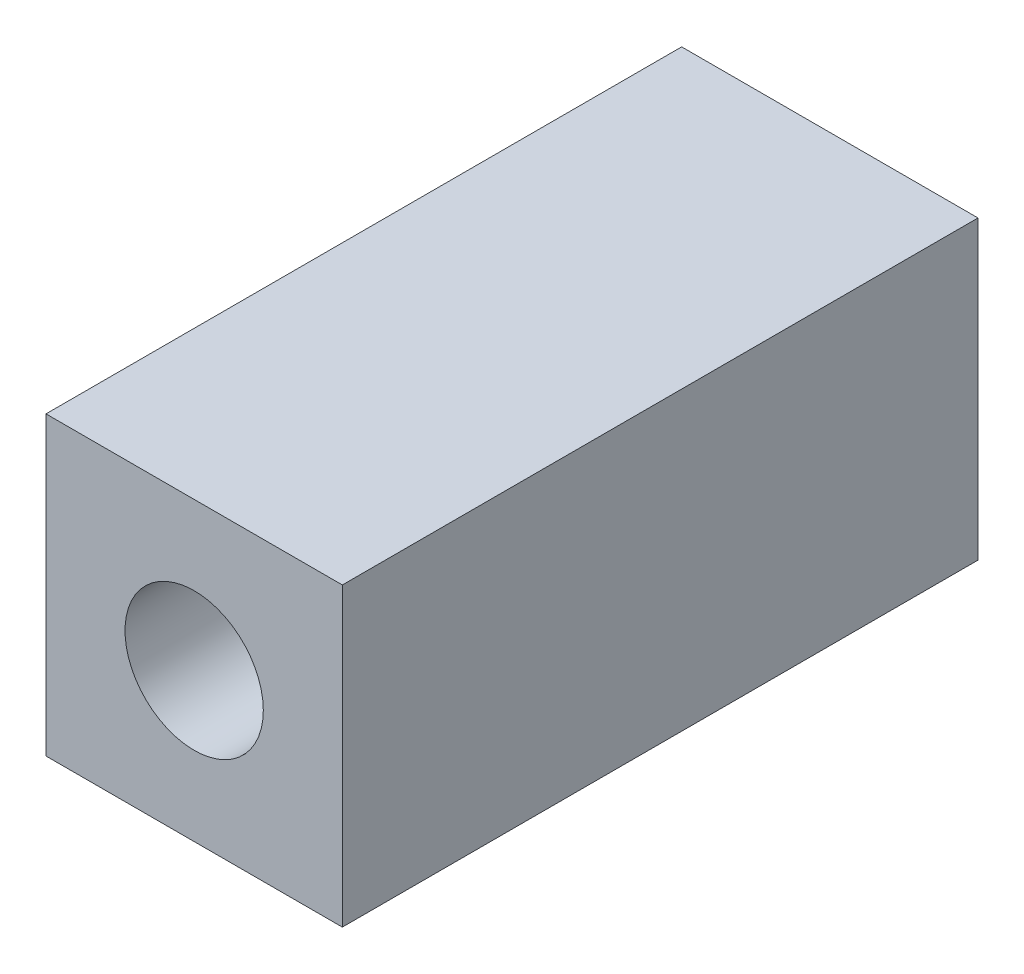
SolidWorks part; units mm, degrees
ref_plane "Front Plane" through (0, 0, 0) normal (0, 0, 1) x (1, 0, 0)
ref_plane "Top Plane" through (0, 0, 0) normal (0, 1, 0) x (1, 0, 0)
ref_plane "Right Plane" through (0, 0, 0) normal (1, 0, 0) x (0, 0, -1)
sketch "Sketch1" plane through (0, 0, 0) normal (0, 0, 1) x (1, 0, 0)
  line L1 (3, 3) -> (-3, 3)
  line L2 (3, 3) -> (3, -3)
  line L3 (3, -3) -> (-3, -3)
  line L4 (-3, 3) -> (-3, -3)
  line L5 (3, 3) -> (-3, -3) construction
  line L6 (3, -3) -> (-3, 3) construction
  circle A0 centre (0, 0) radius 1.4
  point P0 (0, 0)
  dimension "D1" = 2.8
  dimension "D2" = 6
  dimension "D3" = 6
extrude "Boss-Extrude1" add sketch "Sketch1" along normal blind 12.87
